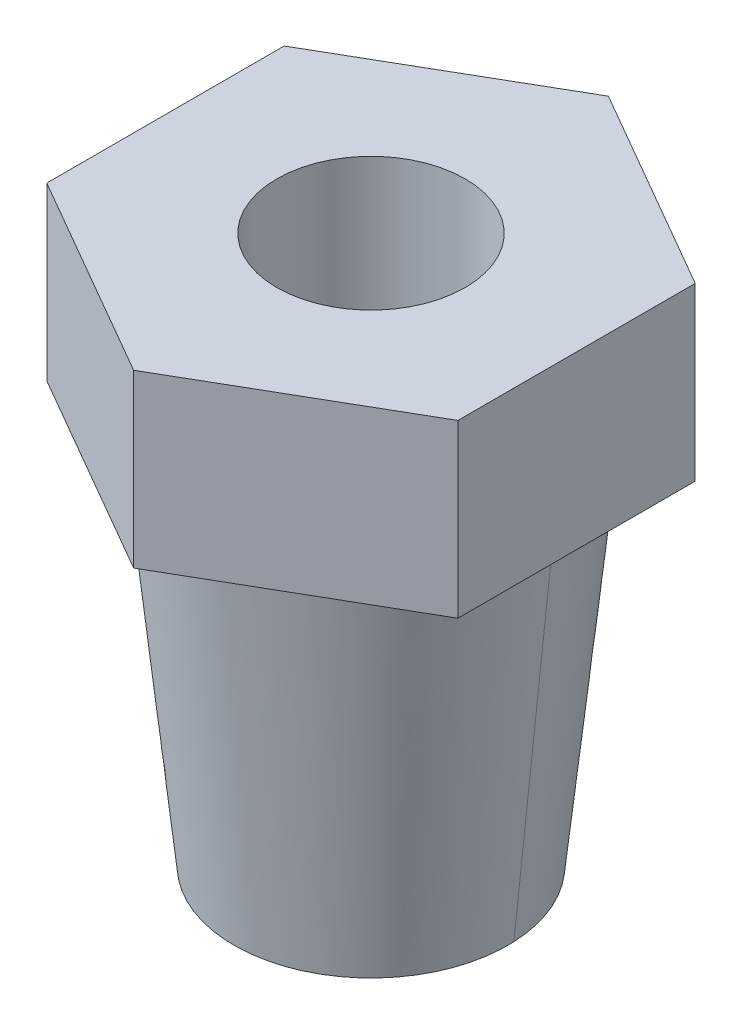
SolidWorks part; units mm, degrees
ref_plane "Plano frontal" through (0, 0, 0) normal (0, 0, 1) x (1, 0, 0)
ref_plane "Plano superior" through (0, 0, 0) normal (0, 1, 0) x (1, 0, 0)
ref_plane "Plano direito" through (0, 0, 0) normal (1, 0, 0) x (0, 0, -1)
sketch "Esboço1" plane through (0, 0, 0) normal (0, 1, 0) x (1, 0, 0)
  line L7 (0, -6.9282) -> (6, -3.4641)
  line L8 (6, -3.4641) -> (6, 3.4641)
  line L9 (6, 3.4641) -> (0, 6.9282)
  line L10 (0, 6.9282) -> (-6, 3.4641)
  line L11 (-6, 3.4641) -> (-6, -3.4641)
  line L12 (-6, -3.4641) -> (0, -6.9282)
  circle A0 centre (0, 0) radius 6 construction
  dimension "D1" = 12
extrude "Ressalto-extrusão1" add sketch "Esboço1" against normal blind 5
sketch "Esboço2" plane through (0, -5, 0) normal (0, -1, 0) x (1, 0, 0)
  circle A0 centre (0, 0) radius 4
  dimension "D1" = 8
extrude "Ressalto-extrusão2" add sketch "Esboço2" along normal blind 11 separate body contours A0
sketch "Esboço3" plane through (0, -16, 0) normal (0, -1, 0) x (1, 0, 0)
  circle A0 centre (0, 0) radius 2.75
  dimension "D1" = 5.5
extrude "Corte-extrusão1" cut sketch "Esboço3" against normal blind 22
sketch "Esboço8" plane through (0, -5, 0) normal (0, 1, 0) x (1, 0, 0)
  circle A0 centre (0, 0) radius 4
  circle A1 centre (0, 0) radius 5.1435
  dimension "D1" = 8
  dimension "D2" = 10.287
sketch3d "3DSketch3"
  line L3 (3.9947, -5, -0.2051) -> (5.1382, -5, -0.2051)
  line L4 (5.1382, -5, -0.2051) -> (3.9962, -16, -0.1745)
  line L5 (3.9962, -16, -0.1745) -> (3.9947, -5, -0.2051)
  circle A0 centre (0, -5, 0) radius 4 construction
  circle A3 centre (0, -5, 0) radius 4 construction
  circle A4 centre (0, -16, 0) radius 4 construction
  point P2 (0, -1, 0)
  point P7 (0, -9, 0)
  point P11 (0, -20, 0)
  dimension "D1" = 1.1435
sweep "Varredura1" add profiles "3DSketch3" path edge at (0, -16, -4)
sketch "Esboço20" plane through (0, -5, 0) normal (0, -1, 0) x (1, 0, 0)
  circle A0 centre (0, 0) radius 5.1435
  dimension "D1" = 10.287
curve "Hélice/Espiral3"
